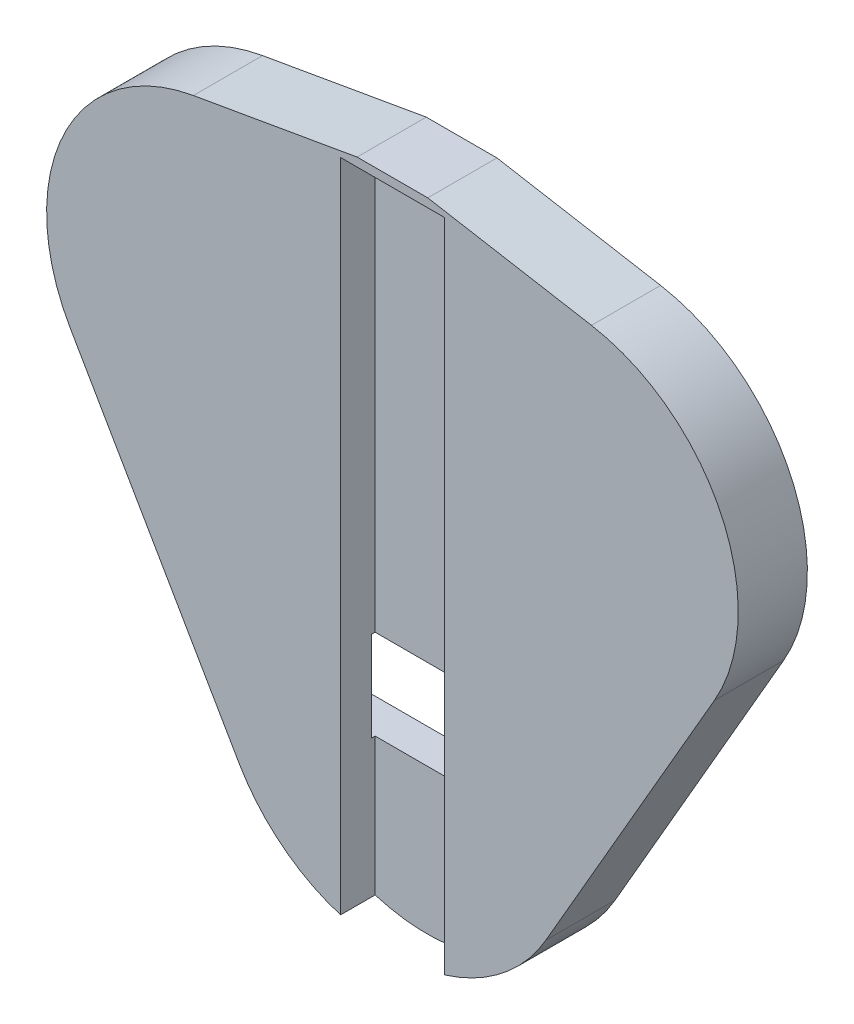
SolidWorks part; units mm, degrees
ref_plane "Front Plane" through (0, 0, 0) normal (0, 0, 1) x (1, 0, 0)
ref_plane "Top Plane" through (0, 0, 0) normal (0, 1, 0) x (1, 0, 0)
ref_plane "Right Plane" through (0, 0, 0) normal (1, 0, 0) x (0, 0, -1)
sketch "Sketch1" plane through (0, 0, 0) normal (0, 0, 1) x (1, 0, 0)
  line L0 (-200000, 0) -> (200119.5956, 0) construction
  line L1 (0, -200000) -> (0, 200075.1119) construction
  line L2 (-2.0433, 17.3792) -> (-11.5123, 15.7265) construction
  line L3 (-2.0433, 17.3792) -> (2.0433, 17.3792) construction
  line L4 (2.0433, 17.3792) -> (11.5123, 15.7265) construction
  line L5 (8.8768, -16.3833) -> (18.6268, 0.5042) construction
  line L6 (-8.8768, -16.3833) -> (-18.6268, 0.5042) construction
  line L7 (-200000, 0) -> (200119.5956, 0)
  line L8 (0, -200000) -> (0, 200075.1119)
  line L9 (-2.0433, 17.3792) -> (-11.5123, 15.7265)
  line L10 (-2.0433, 17.3792) -> (2.0433, 17.3792)
  line L11 (2.0433, 17.3792) -> (11.5123, 15.7265)
  line L12 (8.8768, -16.3833) -> (18.6268, 0.5042)
  line L13 (-8.8768, -16.3833) -> (-18.6268, 0.5042)
  arc A0 (18.6268, 0.5042) -> (11.5123, 15.7265) centre (9.75, 5.6292) ccw construction
  arc A1 (-8.8768, -16.3833) -> (8.8768, -16.3833) centre (0, -11.2583) ccw construction
  arc A2 (-11.5123, 15.7265) -> (-18.6268, 0.5042) centre (-9.75, 5.6292) ccw construction
  arc A3 (18.6268, 0.5042) -> (11.5123, 15.7265) centre (9.75, 5.6292) ccw
  arc A4 (-8.8768, -16.3833) -> (8.8768, -16.3833) centre (0, -11.2583) ccw
  arc A5 (-11.5123, 15.7265) -> (-18.6268, 0.5042) centre (-9.75, 5.6292) ccw
extrude "Boss-Extrude1" add sketch "Sketch1" along normal up to surface (4 mm away) from surface contours A5 L13 A4 L12 A3 L11 L10 L9
sketch "Sketch2" plane through (0, 0, 0) normal (0, 1, 0) x (1, 0, 0)
  line L0 (3, 31.5) -> (3, 36.5) construction
  line L1 (-3, 31.5) -> (3, 31.5) construction
  line L2 (-3, 36.5) -> (-3, 31.5) construction
  line L3 (3, 31.5) -> (3, 36.5)
  line L4 (-3, 31.5) -> (3, 31.5)
  line L5 (-3, 36.5) -> (-3, 31.5)
  line L6 (-3, 34.5) -> (3, 34.5)
  line L7 (-2.0433, 32.5) -> (2.0433, 32.5) construction
  dimension "D1" = 2
extrude "Cut-Extrude1" cut sketch "Sketch2" against normal through all and the other way up to surface contours L6 L5 L4 L3
sketch "Sketch4" plane through (0, 0, -36.5) normal (0, 0, -1) x (-1, 0, 0)
  line L0 (9, -13) -> (9, -3) construction
  line L1 (9, -3) -> (5, -3) construction
  line L2 (5, -3) -> (5, -8) construction
  line L3 (5, -8) -> (-5, -8) construction
  line L4 (-5, -8) -> (-5, -3) construction
  line L5 (-5, -3) -> (-9, -3) construction
  line L6 (-9, -3) -> (-9, -13) construction
  line L7 (-9, -13) -> (9, -13) construction
  line L8 (9.1, -13.1) -> (9.1, -2.9)
  line L9 (9.1, -2.9) -> (4.9, -2.9)
  line L10 (4.9, -2.9) -> (4.9, -7.9)
  line L11 (4.9, -7.9) -> (-4.9, -7.9)
  line L12 (-4.9, -7.9) -> (-4.9, -2.9)
  line L13 (-4.9, -2.9) -> (-9.1, -2.9)
  line L14 (-9.1, -2.9) -> (-9.1, -13.1)
  line L15 (-9.1, -13.1) -> (9.1, -13.1)
  dimension "D1" = 0.1
extrude "Cut-Extrude2" cut sketch "Sketch4" against normal blind 2.2 contours L14 L15 L8 L9 L10 L11 L12 L13
